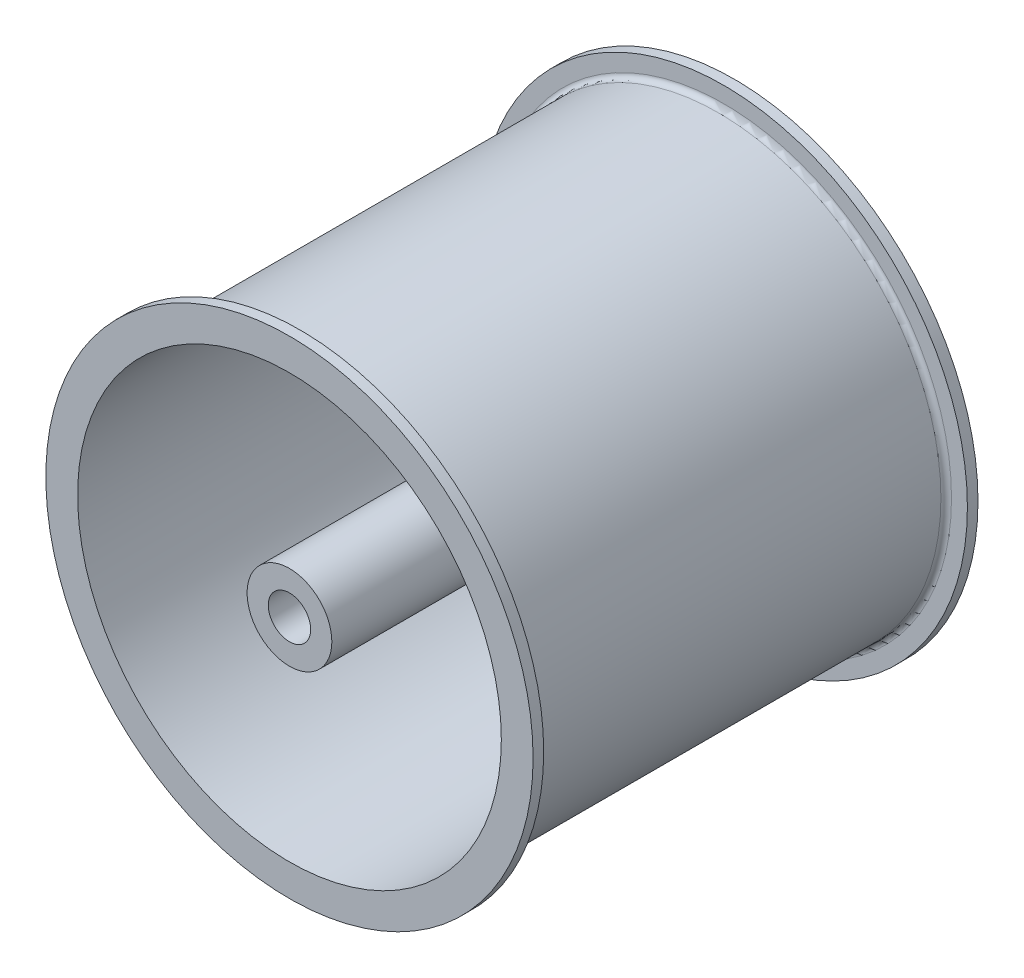
SolidWorks part; units mm, degrees
ref_plane "Front Plane" through (0, 0, 0) normal (0, 0, 1) x (1, 0, 0)
ref_plane "Top Plane" through (0, 0, 0) normal (0, 1, 0) x (1, 0, 0)
ref_plane "Right Plane" through (0, 0, 0) normal (1, 0, 0) x (0, 0, -1)
sketch "Sketch1" plane through (0, 0, 0) normal (0, 0, 1) x (1, 0, 0)
  circle A0 centre (0, 0) radius 21
extrude "Extrude-Thin1" add sketch "Sketch1" along normal blind 40 thin thin type one direction reverse wall 1
sketch "Sketch2" plane through (0, 0, 40) normal (0, 0, 1) x (1, 0, 0)
  circle A2 centre (0, 0) radius 23
  circle A3 centre (0, 0) radius 23
  dimension "D1" = 2
extrude "Extrude-Thin2" add sketch "Sketch2" along normal blind 1 thin thin type one direction reverse wall 3
fillet "Fillet1" radius 0.5 1 edges at (21, 0, 40)
ref_plane "Symmetry-Plane" through (0, 0, 20) normal (0, 0, 1) x (1, 0, 0)
mirror "Mirror1" about plane through (0, 0, 20) normal (0, 0, 1) of "Extrude-Thin2", "Fillet1"
sketch "Sketch3" plane through (0, 0, 0) normal (0, 0, 1) x (1, 0, 0)
  circle A0 centre (0, 0) radius 20 construction
  circle A1 centre (0, 0) radius 20
extrude "Boss-Extrude1" add sketch "Sketch3" along normal blind 1 from offset 11
sketch "Sketch4" plane through (0, 0, 11) normal (0, 0, -1) x (-1, 0, 0)
  circle A0 centre (0, 0) radius 4
extrude "Extrude-Thin3" add sketch "Sketch4" along normal blind 2 thin thin type one direction reverse wall 1
fillet "Fillet2" radius 0.1 4 edges at (-3, 0, 11) (-3, 0, 9) (-4, 0, 9) (4, 0, 11)
sketch "Sketch5" plane through (0, 0, 11) normal (0, 0, -1) x (-1, 0, 0)
  circle A0 centre (0, 0) radius 2
extrude "Cut-Extrude1" cut sketch "Sketch5" against normal up to next
sketch "Sketch6" plane through (0, 0, 11) normal (0, 0, -1) x (-1, 0, 0)
  circle A0 centre (14, 0) radius 4
  circle A1 centre (0, 0) radius 20
  circle A2 centre (0, 0) radius 20
  circle A3 centre (9.8995, -9.8995) radius 4
  circle A4 centre (0, -14) radius 4
  circle A5 centre (-9.8995, -9.8995) radius 4
  circle A6 centre (-14, 0) radius 4
  circle A7 centre (-9.8995, 9.8995) radius 4
  circle A8 centre (0, 14) radius 4
  circle A9 centre (9.8995, 9.8995) radius 4
  point P21 (0, 0)
  dimension "D2" = 14
  dimension "D3" = 8
  dimension "D1" = 0
  dimension "D4" = 8
extrude "Cut-Extrude2" cut sketch "Sketch6" against normal up to next contours A0 | A9 | A8 | A7 | A6 | A5 | A4 | A3
fillet "Fillet3" radius 0.1 16 edges at (-10, 0, 12) (-18, 0, 11) (-13.8995, -9.8995, 11) (-5.8995, -9.8995, 12) (-4, -14, 11) (4, -14, 12) (5.8995, -9.8995, 11) (13.8995, -9.8995, 12) (-4, 14, 11) (4, 14, 12) (18, 0, 12) (10, 0, 11) (13.8995, 9.8995, 12) (5.8995, 9.8995, 11) (-5.8995, 9.8995, 12) (-13.8995, 9.8995, 11)
fillet "Fillet4" radius 1 1 edges at (20, 0, 11)
sketch "Sketch7" plane through (0, 0, 12) normal (0, 0, 1) x (1, 0, 0)
  circle A0 centre (0, 0) radius 2 construction
  circle A1 centre (0, 0) radius 2
  circle A2 centre (0, 0) radius 4
  dimension "D2" = 4
  dimension "D1" = 2
extrude "Boss-Extrude2" add sketch "Sketch7" along normal up to surface (29 mm away) up to face at (23, 0, 41)
chamfer "Chamfer1" distance 3 angle 45 1 edges at (4, 0, 12)
fillet "Fillet5" radius 0.001 2 edges at (4, 0, 15) (7, 0, 12)
scale "Scale1" scale about centroid uniform scaling yes scale factor 0.8
